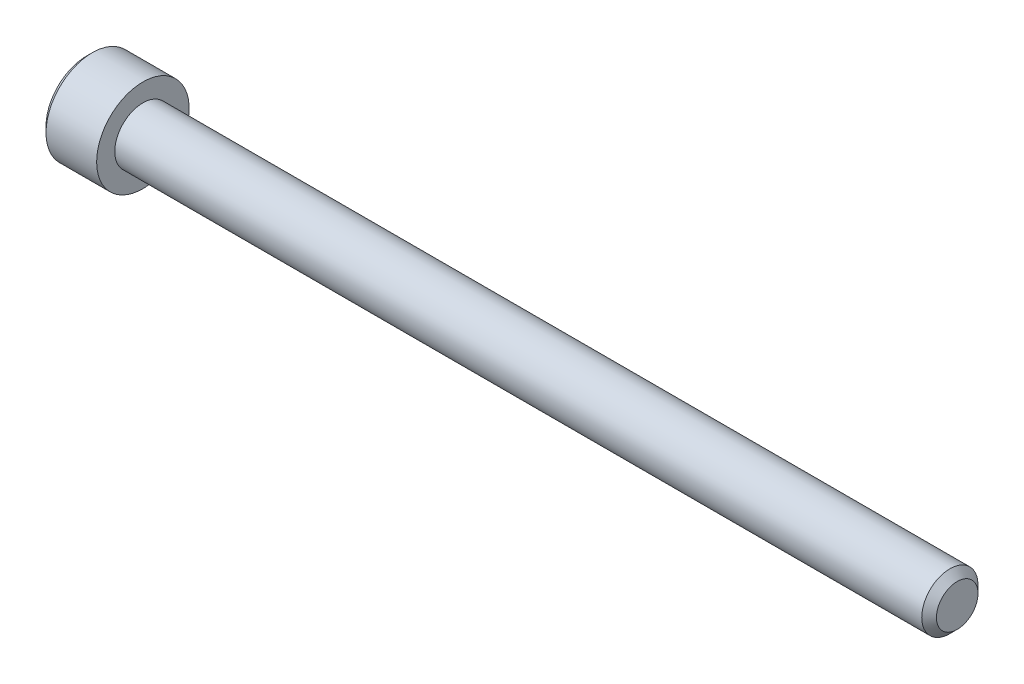
SolidWorks part; units mm, degrees
material "Alloy Steel"
ref_plane "Front Plane" through (0, 0, 0) normal (0, 0, 1) x (1, 0, 0)
ref_plane "Top Plane" through (0, 0, 0) normal (0, 1, 0) x (1, 0, 0)
ref_plane "Right Plane" through (0, 0, 0) normal (1, 0, 0) x (0, 0, -1)
sketch "BodySketch" plane through (0, 0, 0) normal (0, 1, 0) x (1, 0, 0)
  line L0 (0, 2.413) -> (0, 3.9688)
  line L1 (0, 3.9688) -> (-4.3434, 3.9687)
  line L2 (-4.3434, 3.9687) -> (-4.826, 3.4861)
  line L3 (-4.826, 3.4861) -> (-4.826, 0)
  line L4 (0, 2.413) -> (69.2201, 2.413)
  line L5 (69.2201, 2.413) -> (69.85, 1.7831)
  line L6 (69.85, 1.7831) -> (69.85, 0)
  line L7 (-4.826, 0) -> (69.85, 0) construction
  line L8 (-4.826, 0) -> (69.85, 0)
  dimension "Diameter" = 4.826
  dimension "Body_ch_ang" = 45
  dimension "Head_side_ht" = 4.3434
  dimension "Head_ht" = 4.826
  dimension "Head_dia" = 7.9375
  dimension "Length" = 69.85
  dimension "Head_ch_ang" = 45
revolve "BaseBody" add sketch "BodySketch" angle 360 about L7
cosmetic thread "Thread" parameters "Thread_length"=22.225, "Minor_dia"=3.5662
sketch "DriveSketch" plane through (-4.826, 0, 0) normal (-1, 0, 0) x (0, 0, 1)
  line L1 (2.2921, 0) -> (1.146, 1.985)
  line L2 (1.146, 1.985) -> (-1.146, 1.985)
  line L3 (-1.146, 1.985) -> (-2.2921, 0)
  line L4 (-2.2921, 0) -> (-1.146, -1.985)
  line L5 (-1.146, -1.985) -> (1.146, -1.985)
  line L6 (1.146, -1.985) -> (2.2921, 0)
  circle A0 centre (0, 0) radius 1.985 construction
  circle A1 centre (0, 0) radius 3.9687 construction
  dimension "Hex_size" = 3.97
extrude "HexDrive" cut sketch "DriveSketch" against normal blind 2.286
other "Freeze***"
other "PropertyManager"
